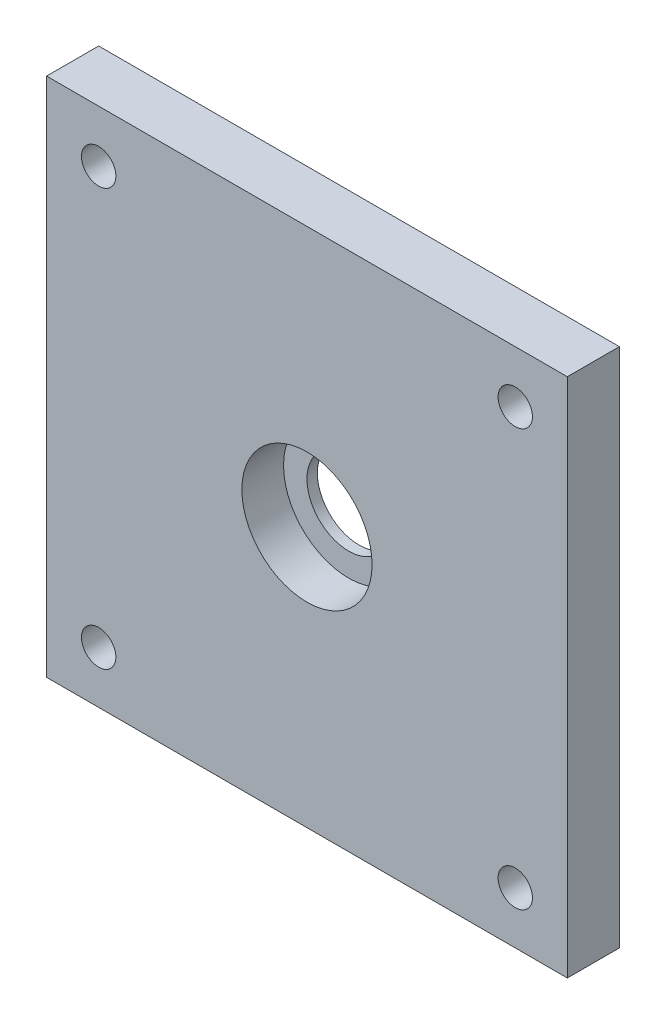
SolidWorks part; units mm, degrees
ref_plane "前视基准面" through (0, 0, 0) normal (0, 0, 1) x (1, 0, 0)
ref_plane "上视基准面" through (0, 0, 0) normal (0, 1, 0) x (1, 0, 0)
ref_plane "右视基准面" through (0, 0, 0) normal (1, 0, 0) x (0, 0, -1)
sketch "草图1" plane through (0, 0, 0) normal (0, 0, 1) x (1, 0, 0)
  line L1 (-25, -25) -> (25, -25)
  line L2 (-25, -25) -> (-25, 25)
  line L3 (-25, 25) -> (25, 25)
  line L4 (25, -25) -> (25, 25)
  line L5 (-25, -25) -> (25, 25) construction
  line L6 (-25, 25) -> (25, -25) construction
  circle A0 centre (-20, -20) radius 1.65
  circle A1 centre (-20, 20) radius 1.65
  circle A2 centre (20, 20) radius 1.65
  circle A3 centre (20, -20) radius 1.65
  circle A4 centre (0, 0) radius 6.25
  point P0 (0, 0)
  point P17 (0, 0)
  dimension "D3" = 3.3
  dimension "D6" = 12.5
  dimension "D1" = 50
  dimension "D2" = 50
  dimension "D4" = 5
  dimension "D5" = 4
extrude "凸台-拉伸1" add sketch "草图1" along normal blind 5
sketch "草图2" plane through (0, 0, 0) normal (0, 0, -1) x (-1, 0, 0)
  circle A0 centre (0, 0) radius 6.25
  circle A1 centre (0, 0) radius 4
  dimension "D1" = 8
extrude "凸台-拉伸2" add sketch "草图2" against normal blind 1
